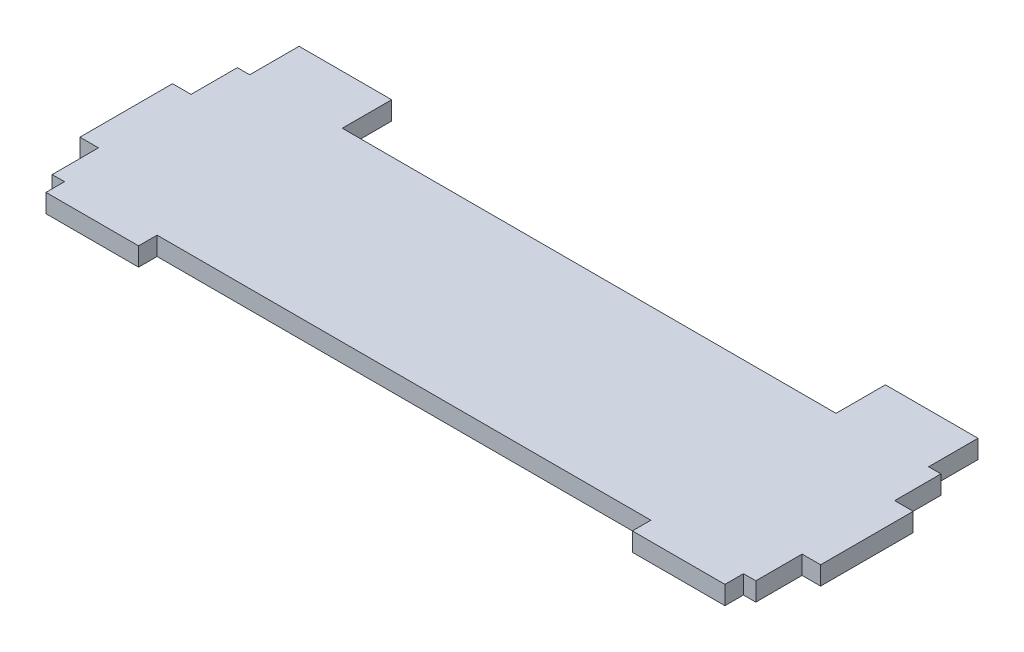
SolidWorks part; units mm, degrees
ref_plane "Front Plane" through (0, 0, 0) normal (0, 0, 1) x (1, 0, 0)
ref_plane "Top Plane" through (0, 0, 0) normal (0, 1, 0) x (1, 0, 0)
ref_plane "Right Plane" through (0, 0, 0) normal (1, 0, 0) x (0, 0, -1)
sketch "Sketch1" plane through (0, 0, 0) normal (0, 1, 0) x (1, 0, 0)
  line L9 (57, 15) -> (57, 7.5)
  line L10 (57, 7.5) -> (60, 7.5)
  line L15 (60, 7.5) -> (60, -7.5)
  line L16 (60, -7.5) -> (57, -7.5)
  line L21 (57, -7.5) -> (57, -15)
  line L23 (-57, -15) -> (-57, -7.5)
  line L24 (-57, -7.5) -> (-60, -7.5)
  line L25 (-60, -7.5) -> (-60, 7.5)
  line L26 (-60, 7.5) -> (-57, 7.5)
  line L27 (-57, 7.5) -> (-57, 15)
  line L28 (-57, 15) -> (-55, 15)
  line L33 (-55, 15) -> (-55, 23)
  line L34 (-55, 23) -> (-40, 23)
  line L39 (-40, 23) -> (-40, 15)
  line L40 (-40, 15) -> (40, 15)
  line L41 (40, 15) -> (40, 23)
  line L42 (40, 23) -> (55, 23)
  line L43 (55, 23) -> (55, 15)
  line L44 (55, 15) -> (57, 15)
  line L45 (-57, -15) -> (-55, -15)
  line L46 (-55, -15) -> (-55, -18)
  line L47 (-55, -18) -> (-40, -18)
  line L48 (-40, -18) -> (-40, -15)
  line L49 (-40, -15) -> (40, -15)
  line L50 (40, -15) -> (40, -18)
  line L51 (40, -18) -> (55, -18)
  line L52 (55, -18) -> (55, -15)
  line L53 (55, -15) -> (57, -15)
  point P0 (0, 0)
  point P17 (-57, 7.5)
  point P18 (-60, 7.5)
  point P19 (57, 7.5)
  point P20 (-57, 15)
  point P21 (57, 15)
  point P22 (57, -7.5)
  point P23 (60, 7.5)
  point P24 (60, -7.5)
  point P25 (-57, -7.5)
  point P26 (57, -15)
  point P27 (-57, -15)
  point P29 (-60, -7.5)
  point P31 (-40, 15)
  point P35 (-40, -15)
  point P36 (-55, 15)
  point P37 (55, 15)
  point P38 (-40, 23)
  point P39 (40, 23)
  point P40 (-55, 23)
  point P41 (55, 23)
  point P42 (40, 15)
  point P43 (40, -15)
  point P44 (55, -15)
  point P64 (-55, -15)
extrude "Boss-Extrude1" add sketch "Sketch1" along normal blind 3
